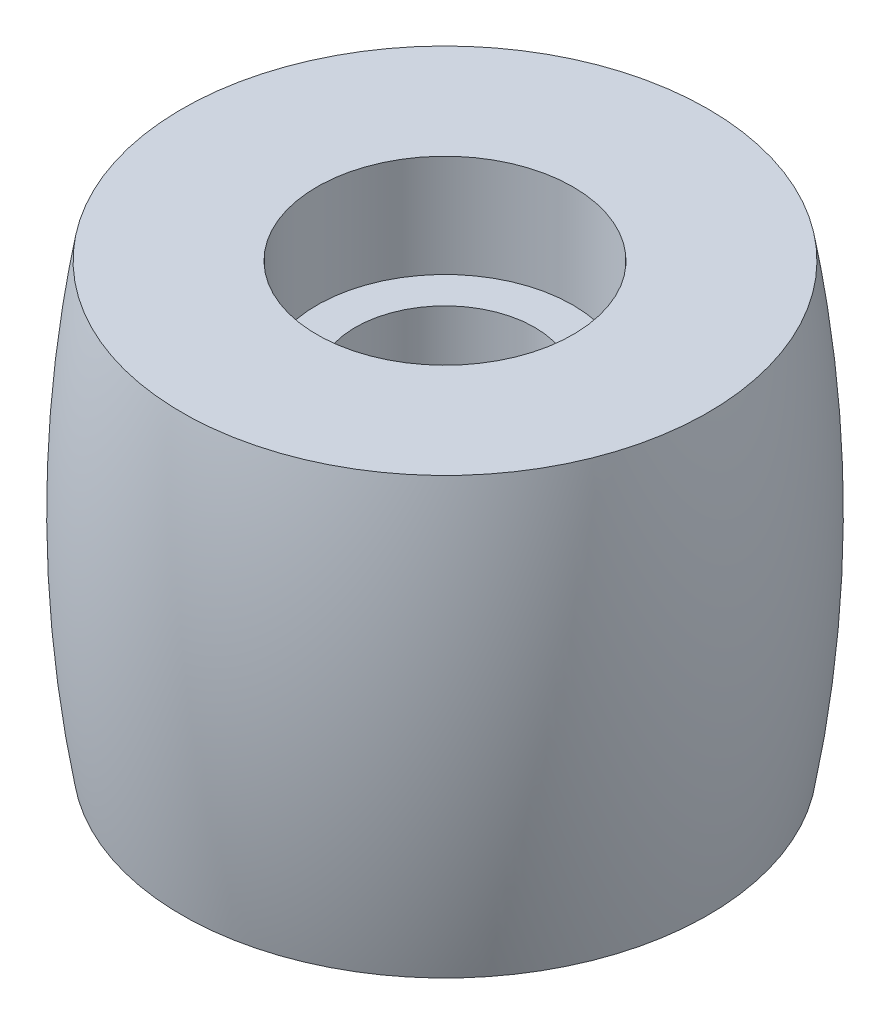
SolidWorks part; units mm, degrees
ref_plane "Front Plane" through (0, 0, 0) normal (0, 0, 1) x (1, 0, 0)
ref_plane "Top Plane" through (0, 0, 0) normal (0, 1, 0) x (1, 0, 0)
ref_plane "Right Plane" through (0, 0, 0) normal (1, 0, 0) x (0, 0, -1)
sketch "Sketch1" plane through (0, 0, 0) normal (0, 0, 1) x (1, 0, 0)
  line L0 (0, -169.065) -> (0, 169.065) construction
  line L1 (-138.68, 0) -> (138.68, 0) construction
  line L2 (3.5, -4.5) -> (3.5, 4.5)
  line L3 (3.5, 4.5) -> (5, 4.5)
  line L4 (5, 4.5) -> (5, 8.5)
  line L5 (5, 8.5) -> (10.2722, 8.5)
  line L6 (3.5, -4.5) -> (5, -4.5)
  line L7 (5, -4.5) -> (5, -8.5)
  line L8 (5, -8.5) -> (10.2722, -8.5)
  arc A0 (10.2722, 8.5) -> (10.2722, -8.5) centre (-39, 0) cw
  point P0 (4.25, 4.5)
  point P4 (0, 0)
  point P7 (0, 0)
  point P10 (3.5, 0)
  point P14 (4.25, -4.5)
  point P19 (11, 0)
  dimension "D1" = 50
  dimension "D2" = 3.5
  dimension "D3" = 5
  dimension "D4" = 11
  dimension "D5" = 17
  dimension "D6" = 4
revolve "Revolve1" add sketch "Sketch1" angle 360 about L0
